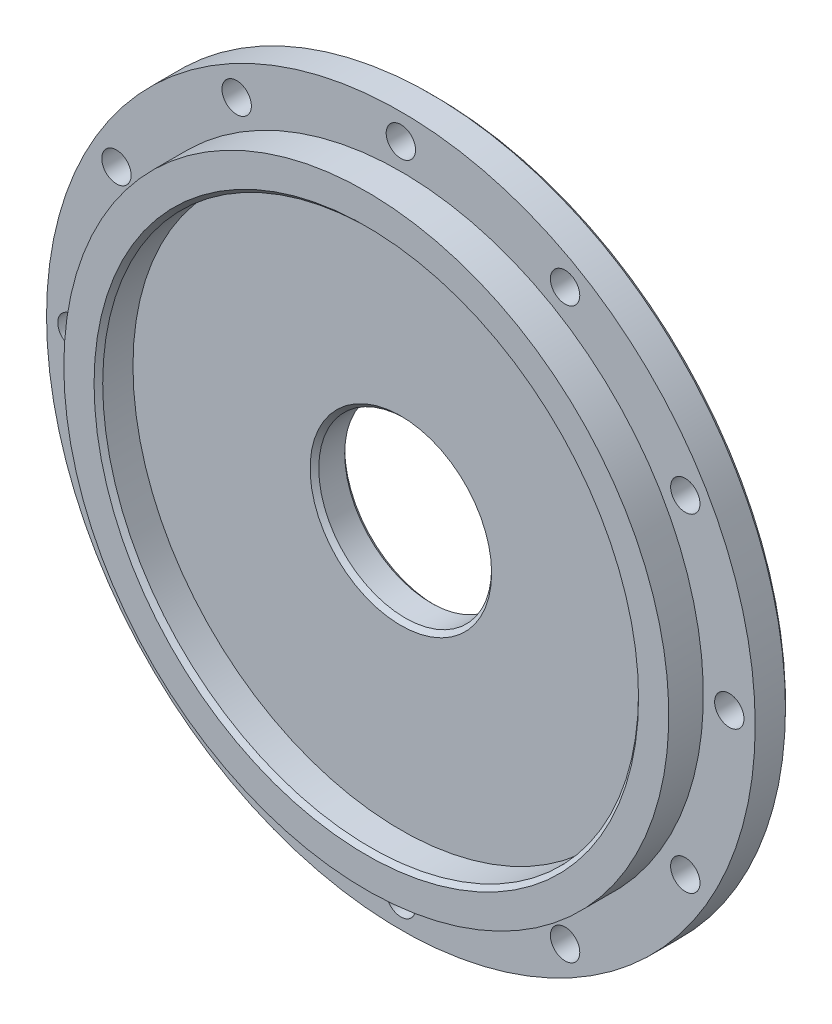
SolidWorks part; units mm, degrees
material "6061-T6 铝合金"
ref_plane "前视基准面" through (0, 0, 0) normal (0, 0, 1) x (1, 0, 0)
ref_plane "上视基准面" through (0, 0, 0) normal (0, 1, 0) x (1, 0, 0)
ref_plane "右视基准面" through (0, 0, 0) normal (1, 0, 0) x (0, 0, -1)
sketch "草图1" plane through (0, 0, 0) normal (1, 0, 0) x (0, 0, -1)
  line L0 (0, 0) -> (-40.6623, 0) construction
  line L1 (0, 0) -> (0, 41)
  line L2 (0, 41) -> (-4, 41)
  line L3 (-4, 41) -> (-4, 35)
  line L4 (-4, 35) -> (-8, 35)
  line L5 (-8, 35) -> (-8, 31)
  line L6 (-8, 31) -> (-4, 31)
  line L7 (-4, 31) -> (-4, 0)
  line L8 (-4, 0) -> (0, 0)
  dimension "D1" = 82
  dimension "D2" = 4
  dimension "D3" = 6
  dimension "D4" = 4
  dimension "D5" = 4
revolve "旋转1" add sketch "草图1" angle 360 about L0
sketch "草图2" plane through (0, 0, 4) normal (0, 0, 1) x (1, 0, 0)
  circle A0 centre (0, 38) radius 1.7
  circle A1 centre (19, 32.909) radius 1.7
  circle A2 centre (32.909, 19) radius 1.7
  circle A3 centre (38, 0) radius 1.7
  circle A4 centre (32.909, -19) radius 1.7
  circle A5 centre (19, -32.909) radius 1.7
  circle A6 centre (0, -38) radius 1.7
  circle A7 centre (-19, -32.909) radius 1.7
  circle A8 centre (-32.909, -19) radius 1.7
  circle A9 centre (-38, 0) radius 1.7
  circle A10 centre (-32.909, 19) radius 1.7
  circle A11 centre (-19, 32.909) radius 1.7
  point P28 (0, 0)
  dimension "D2" = 3.4
  dimension "D1" = 38
  dimension "D3" = 12
extrude "切除-拉伸1" cut sketch "草图2" against normal up to next
sketch "草图3" plane through (0, 0, 0) normal (0, 0, -1) x (-1, 0, 0)
  circle A0 centre (0, 0) radius 10
  dimension "D1" = 20
extrude "切除-拉伸2" cut sketch "草图3" against normal up to next
chamfer "倒角1" distance 0.5 angle 45 4 edges at (10, 0, 4) (-31, 0, 8) (-41, 0, 0) (-10, 0, 0)
